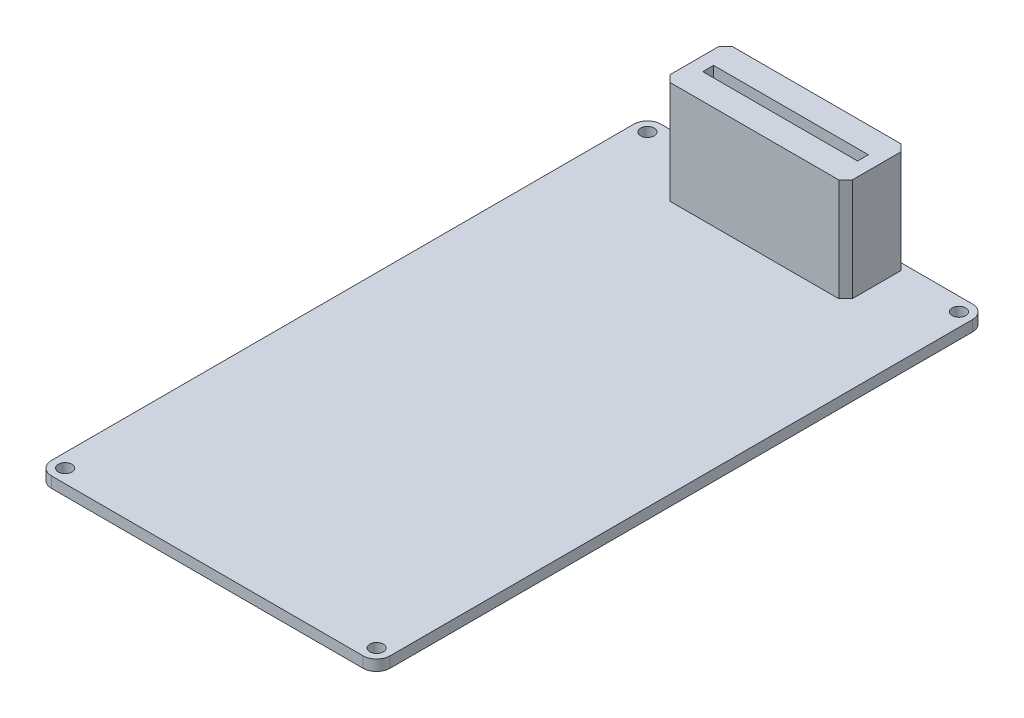
SolidWorks part; units mm, degrees
material "丙烯酸(中高冲击)"
ref_plane "前视基准面" through (0, 0, 0) normal (0, 0, 1) x (1, 0, 0)
ref_plane "上视基准面" through (0, 0, 0) normal (0, 1, 0) x (1, 0, 0)
ref_plane "右视基准面" through (0, 0, 0) normal (1, 0, 0) x (0, 0, -1)
other "Configuration Table"
sketch "草图1" plane through (0, 0, 0) normal (0, 1, 0) x (1, 0, 0)
  line L0 (-23, 45) -> (23, 45)
  line L1 (-25, 45) -> (25, 45) construction
  line L2 (-25, 45) -> (-25, -45) construction
  line L3 (-25, -45) -> (25, -45) construction
  line L4 (25, 45) -> (25, -45) construction
  line L5 (-25, 45) -> (25, -45) construction
  line L6 (-25, -45) -> (25, 45) construction
  line L7 (25, 43) -> (25, -43)
  line L8 (-23, -45) -> (23, -45)
  line L9 (-25, -43) -> (-25, 43)
  arc A0 (-23, 45) -> (-25, 43) centre (-23, 43) ccw
  arc A1 (-25, -43) -> (-23, -45) centre (-23, -43) ccw
  arc A2 (23, -45) -> (25, -43) centre (23, -43) ccw
  arc A3 (25, 43) -> (23, 45) centre (23, 43) ccw
  circle A4 centre (-23, 43) radius 1
  circle A5 centre (23, 43) radius 1
  circle A6 centre (-23, -43) radius 1
  circle A7 centre (23, -43) radius 1
  point P0 (0, 0)
  dimension "D3" = 4
  dimension "D4" = 4
  dimension "D5" = 4
  dimension "D6" = 4
  dimension "D7" = 2
  dimension "D8" = 2
  dimension "D9" = 2
  dimension "D10" = 2
  dimension "D1" = 50
  dimension "D2" = 90
extrude "凸台-拉伸1" add sketch "草图1" along normal blind 1.6
sketch "草图2" plane through (0, 0, 0) normal (0, 1, 0) x (1, 0, 0)
  line L0 (23, 45) -> (-23, 45) construction
  line L1 (-13.46, 45) -> (13.46, 45)
  line L2 (-13.46, 45) -> (-13.46, 35.8)
  line L3 (-13.46, 35.8) -> (13.46, 35.8)
  line L4 (13.46, 45) -> (13.46, 35.8)
  point P6 (0, 35.8)
  dimension "D1" = 26.92
  dimension "D2" = 9.2
extrude "凸台-拉伸2" add sketch "草图2" along normal blind 15.2 from surface at 1.6 starting at face at (-23, 1.6, 44)
sketch "草图3" plane through (0, 0, 0) normal (0, 1, 0) x (1, 0, 0)
  line L1 (-11.43, 41.2) -> (11.43, 41.2)
  line L2 (-11.43, 41.2) -> (-11.43, 39.6)
  line L3 (-11.43, 39.6) -> (11.43, 39.6)
  line L4 (11.43, 41.2) -> (11.43, 39.6)
  line L5 (13.46, 45) -> (13.46, 35.8) construction
  point P4 (0, 39.6)
  point P10 (13.46, 40.4)
  point P11 (11.43, 40.4)
  dimension "D1" = 22.86
  dimension "D2" = 1.6
extrude "切除-拉伸1" cut sketch "草图3" against normal blind 9 from surface at 16.8 starting at face at (0, 16.8, -40.4)
sketch "草图4" plane through (0, 0, 0) normal (0, 0, 1) x (1, 0, 0)
  line L0 (-13.46, 16.8) -> (-13.46, 1.6) construction
  line L1 (13.46, 1.6) -> (-13.46, 1.6)
  line L2 (13.46, 1.6) -> (13.46, 2.6)
  line L3 (13.46, 2.6) -> (-13.46, 2.6)
  line L4 (-13.46, 1.6) -> (-13.46, 2.6)
  dimension "D1" = 1
extrude "切除-拉伸2" cut sketch "草图4" along normal blind 0.1 from surface at -45 starting at face at (0, 5, -45)
sketch "草图5" plane through (0, 0, 0) normal (0, 1, 0) x (1, 0, 0)
  line L0 (13.46, 35.8) -> (13.46, 36.8)
  line L1 (13.46, 44.9) -> (13.46, 35.8) construction
  line L2 (13.46, 36.8) -> (12.46, 35.8)
  line L3 (13.46, 35.8) -> (-13.46, 35.8) construction
  line L4 (12.46, 35.8) -> (13.46, 35.8)
  line L5 (13.46, 45) -> (13.46, 44)
  line L6 (13.46, 45) -> (13.46, 35.8) construction
  line L7 (13.46, 44) -> (12.46, 45)
  line L8 (23, 45) -> (-23, 45) construction
  line L9 (12.46, 45) -> (13.46, 45)
  line L10 (-13.46, 45) -> (-13.46, 44)
  line L11 (-13.46, 35.8) -> (-13.46, 45) construction
  line L12 (-13.46, 44) -> (-12.46, 45)
  line L13 (-13.46, 45) -> (13.46, 45) construction
  line L14 (-12.46, 45) -> (-13.46, 45)
  line L15 (-13.46, 35.8) -> (-12.46, 35.8)
  line L16 (13.46, 35.8) -> (-13.46, 35.8) construction
  line L17 (-12.46, 35.8) -> (-13.46, 36.8)
  line L18 (-13.46, 36.8) -> (-13.46, 35.8)
  dimension "D1" = 1
  dimension "D2" = 1
  dimension "D3" = 1
  dimension "D4" = 1
  dimension "D5" = 1
  dimension "D6" = 1
  dimension "D7" = 1
  dimension "D8" = 1
extrude "切除-拉伸3" cut sketch "草图5" along normal up to surface (15.2 mm away) from surface at 1.6 up to face at (0, 16.8, -40.4) starting at face at (0, 1.6, -40.35)
